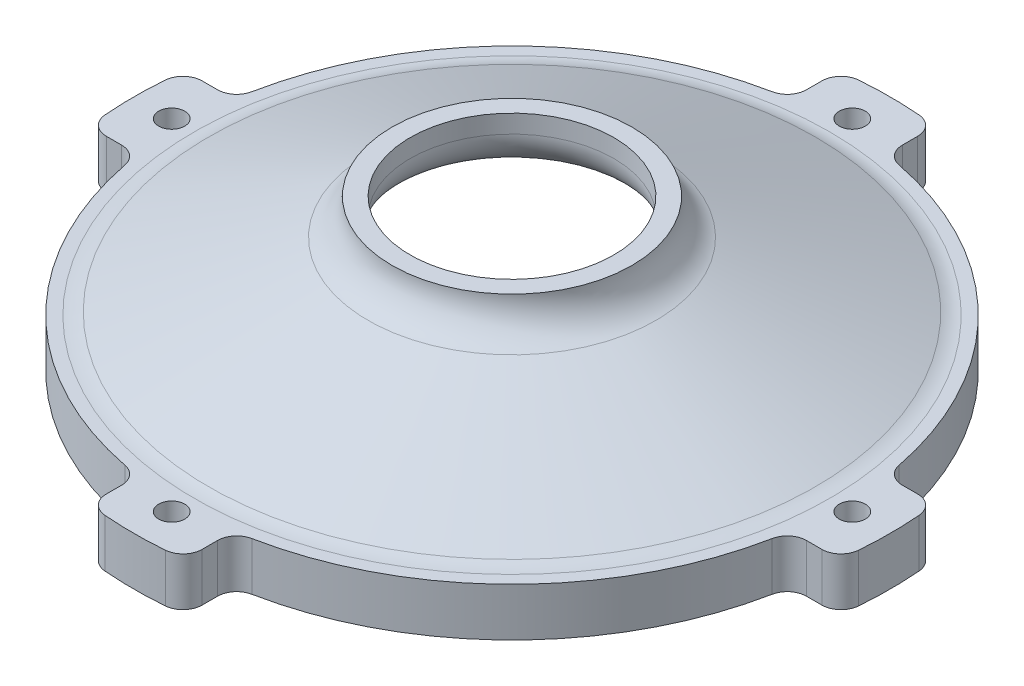
SolidWorks part; units mm, degrees
material "Nylon 101"
ref_plane "Front Plane" through (0, 0, 0) normal (0, 0, 1) x (1, 0, 0)
ref_plane "Top Plane" through (0, 0, 0) normal (0, 1, 0) x (1, 0, 0)
ref_plane "Right Plane" through (0, 0, 0) normal (1, 0, 0) x (0, 0, -1)
sketch "Sketch2" plane through (0, 0, 0) normal (0, 0, 1) x (1, 0, 0)
  line L0 (0, 0) -> (0, 25) construction
  line L1 (50, 0) -> (62.5, 0)
  line L2 (16.8275, 25) -> (16.8275, 22)
  line L5 (20.7925, 16.1149) -> (46.035, 5.8851)
  line L6 (50, 0) -> (50, -25) construction
  line L7 (62.5, 0) -> (62.5, 7.9825)
  line L8 (62.5, 7.9825) -> (52.5, 7.9825)
  line L9 (16.8275, 25) -> (19.8275, 25)
  line L10 (23.7925, 19.1149) -> (50.115, 8.4474)
  arc A0 (16.8275, 22) -> (20.7925, 16.1149) centre (23.1775, 22) ccw
  arc A1 (50, 0) -> (46.035, 5.8851) centre (43.65, 0) ccw
  arc A2 (52.5, 7.9825) -> (50.115, 8.4474) centre (52.5, 14.3325) cw
  arc A3 (19.8275, 25) -> (23.7925, 19.1149) centre (26.1775, 25) ccw
  dimension "D6" = 6.35
  dimension "D7" = 6.35
  dimension "D1" = 25
  dimension "D2" = 100
  dimension "D3" = 125
  dimension "D4" = 33.655
  dimension "D5" = 3
  dimension "D8" = 3
  dimension "D9" = 10
revolve "Revolve1" add sketch "Sketch2" angle 360 about L0
hole_wizard "#18 (0.1695) Diameter Hole1" positions "Sketch4" profile "Sketch3" hole size "#18" standard "ANSI Inch"
sketch "Sketch4" plane through (0, 0, 0) normal (0, -1, 0) x (-1, 0, 0)
  line L0 (0, 50) -> (0, 62.5) construction
  line L1 (0, 56.25) -> (0, -56.25) construction
  line L4 (-56.25, 0) -> (56.25, 0) construction
  circle A0 centre (0, 0) radius 50 construction
  circle A2 centre (0, 0) radius 62.5 construction
  point P12 (0, 56.25)
  point P31 (0, -56.25)
  point P34 (-56.25, 0)
  point P35 (56.25, 0)
sketch "Sketch3" plane through (0, 0, -56.25) normal (1, 0, 0) x (0, 0, -1)
  line L0 (0, 0) -> (0, 39.3934)
  line L1 (0, 39.3934) -> (2.1526, 38.1)
  line L2 (2.1526, 38.1) -> (2.1526, 0)
  line L5 (2.1526, 0) -> (0, 0)
  line L10 (0, 39.3934) -> (-2.1527, 38.1) construction
  line L11 (0, -6.35) -> (0, 107.95) construction
  dimension "Hole Dia." = 4.3053
  dimension "Hole Depth" = 38.1
  dimension "Drill Angle" = 118
extrude "Cut-Extrude1" cut sketch "Sketch5" against normal blind 28
sketch "Sketch5" plane through (0, 7.9825, 0) normal (0, 1, 0) x (1, 0, 0)
  line L0 (0, 0) -> (0, 62.5) construction
  line L1 (0, 0) -> (-62.5, 0) construction
  line L2 (-44.1942, 44.1942) -> (-38.5373, 38.5373) construction
  line L3 (-56.5976, 7.921) -> (-59.1349, 7.921)
  line L4 (-7.921, 56.5976) -> (-7.921, 59.1349)
  line L5 (7.921, 56.5976) -> (7.921, 59.1349)
  line L6 (56.5976, 7.921) -> (59.1349, 7.921)
  line L7 (56.5976, -7.921) -> (59.1349, -7.921)
  line L8 (7.921, -56.5976) -> (7.921, -59.1349)
  line L9 (-7.921, -56.5976) -> (-7.921, -59.1349)
  line L10 (-56.5976, -7.921) -> (-59.1349, -7.921)
  arc A0 (-62.2997, 5) -> (-5, 62.2997) centre (0, 0) cw
  arc A2 (-53.4819, 10.4852) -> (-56.5976, 7.921) centre (-56.5976, 11.096) cw
  arc A3 (-10.4852, 53.4819) -> (-7.921, 56.5976) centre (-11.096, 56.5976) ccw
  arc A4 (-53.4819, 10.4852) -> (-10.4852, 53.4819) centre (0, 0) cw
  arc A5 (-7.921, 59.1349) -> (-5, 62.2997) centre (-4.746, 59.1349) cw
  arc A6 (-59.1349, 7.921) -> (-62.2997, 5) centre (-59.1349, 4.746) ccw
  arc A7 (5, 62.2997) -> (62.2997, 5) centre (0, 0) cw
  arc A8 (7.921, 59.1349) -> (5, 62.2997) centre (4.746, 59.1349) ccw
  arc A9 (10.4852, 53.4819) -> (7.921, 56.5976) centre (11.096, 56.5976) cw
  arc A10 (10.4852, 53.4819) -> (53.4819, 10.4852) centre (0, 0) cw
  arc A11 (53.4819, 10.4852) -> (56.5976, 7.921) centre (56.5976, 11.096) ccw
  arc A12 (59.1349, 7.921) -> (62.2997, 5) centre (59.1349, 4.746) cw
  arc A13 (62.2997, -5) -> (5, -62.2997) centre (0, 0) cw
  arc A14 (59.1349, -7.921) -> (62.2997, -5) centre (59.1349, -4.746) ccw
  arc A15 (53.4819, -10.4852) -> (56.5976, -7.921) centre (56.5976, -11.096) cw
  arc A16 (53.4819, -10.4852) -> (10.4852, -53.4819) centre (0, 0) cw
  arc A17 (10.4852, -53.4819) -> (7.921, -56.5976) centre (11.096, -56.5976) ccw
  arc A18 (7.921, -59.1349) -> (5, -62.2997) centre (4.746, -59.1349) cw
  arc A19 (-5, -62.2997) -> (-62.2997, -5) centre (0, 0) cw
  arc A20 (-7.921, -59.1349) -> (-5, -62.2997) centre (-4.746, -59.1349) ccw
  arc A21 (-10.4852, -53.4819) -> (-7.921, -56.5976) centre (-11.096, -56.5976) cw
  arc A22 (-10.4852, -53.4819) -> (-53.4819, -10.4852) centre (0, 0) cw
  arc A23 (-53.4819, -10.4852) -> (-56.5976, -7.921) centre (-56.5976, -11.096) ccw
  arc A24 (-59.1349, -7.921) -> (-62.2997, -5) centre (-59.1349, -4.746) cw
  point P60 (0, 0)
